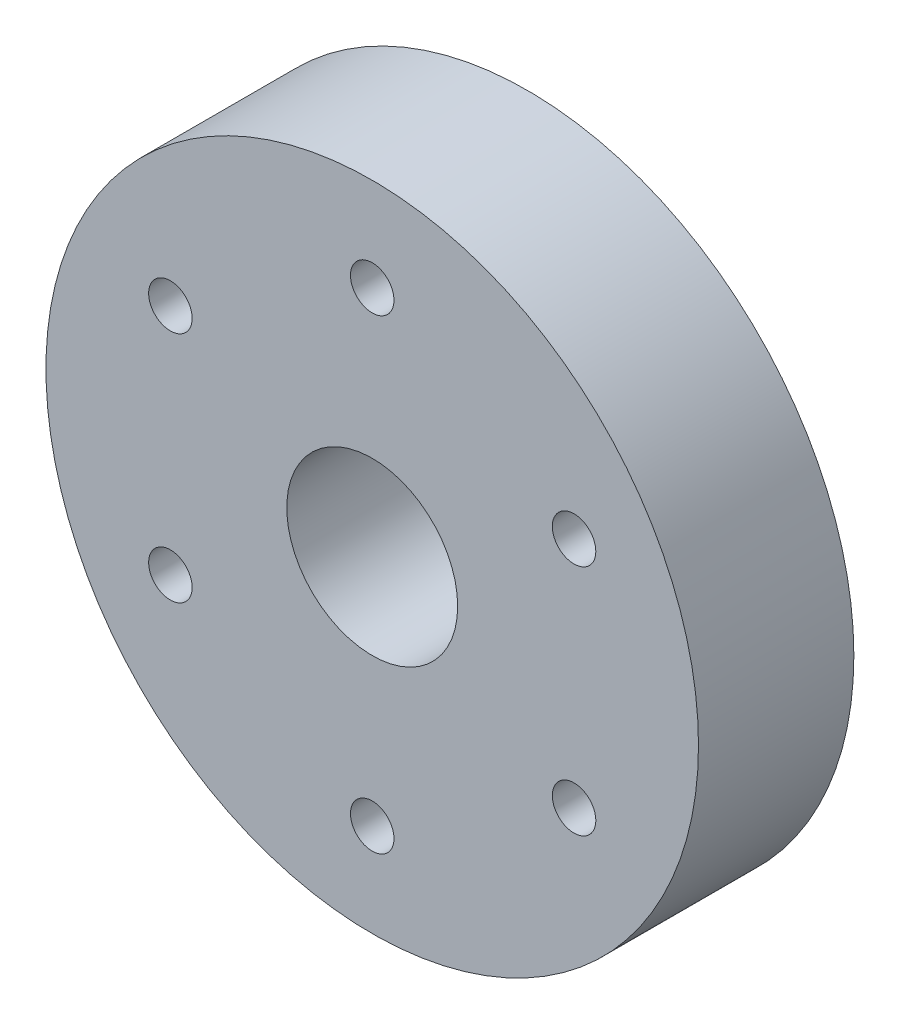
SolidWorks part; units mm, degrees
ref_plane "前视基准面" through (0, 0, 0) normal (0, 0, 1) x (1, 0, 0)
ref_plane "上视基准面" through (0, 0, 0) normal (0, 1, 0) x (1, 0, 0)
ref_plane "右视基准面" through (0, 0, 0) normal (1, 0, 0) x (0, 0, -1)
sketch "草图1" plane through (0, 0, 0) normal (0, 0, 1) x (1, 0, 0)
  circle A0 centre (0, 0) radius 21
  dimension "D1" = 42
extrude "凸台-拉伸1" add sketch "草图1" along normal blind 10
sketch "草图2" plane through (0, 0, 10) normal (0, 0, 1) x (1, 0, 0)
  line L0 (0, 0) -> (12.9904, 7.5) construction
  line L1 (0, 0) -> (15.7679, 0) construction
  circle A0 centre (12.9904, 7.5) radius 1.4
  dimension "D1" = 2.8
  dimension "D2" = 15
  dimension "D3" = 30
extrude "切除-拉伸1" cut sketch "草图2" against normal through all
pattern_circular "阵列(圆周)1" count 6 over 360 about axis through (0, 0, 0) along (0, 0, 1) of "切除-拉伸1"
sketch "草图3" plane through (0, 0, 10) normal (0, 0, 1) x (1, 0, 0)
  circle A0 centre (0, 0) radius 5.5
  dimension "D1" = 11
extrude "切除-拉伸2" cut sketch "草图3" against normal through all
